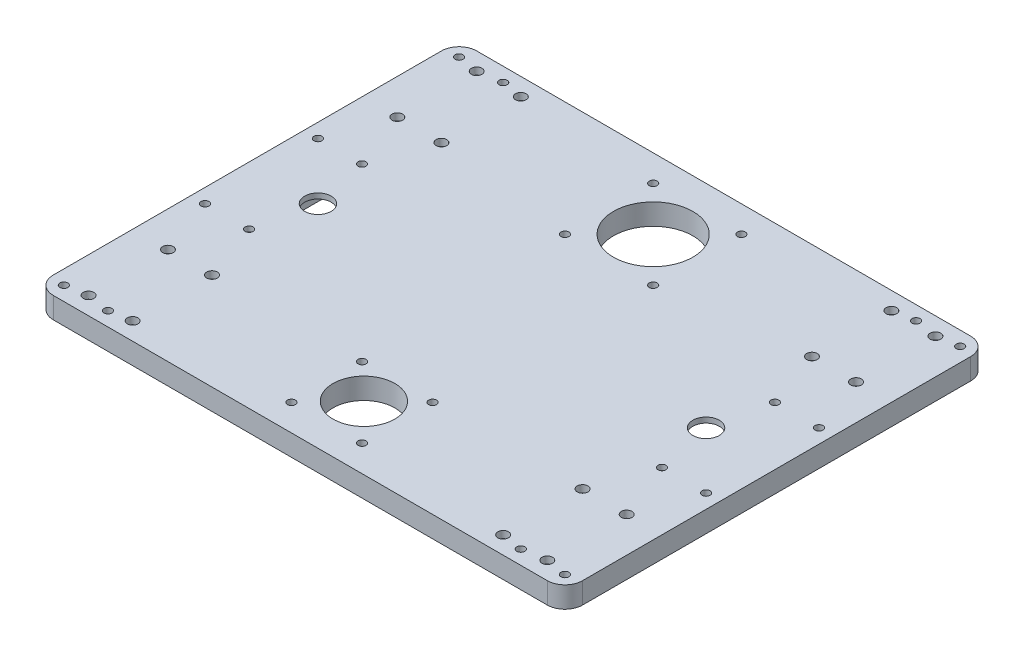
SolidWorks part; units mm, degrees
ref_plane "Front Plane" through (0, 0, 0) normal (0, 0, 1) x (1, 0, 0)
ref_plane "Top Plane" through (0, 0, 0) normal (0, 1, 0) x (1, 0, 0)
ref_plane "Right Plane" through (0, 0, 0) normal (1, 0, 0) x (0, 0, -1)
sketch "Sketch1" plane through (0, 0, 0) normal (0, 1, 0) x (1, 0, 0)
  line L1 (-150, 120) -> (150, 120)
  line L2 (-150, 120) -> (-150, -120)
  line L3 (-150, -120) -> (150, -120)
  line L4 (150, 120) -> (150, -120)
  dimension "D1" = 300
  dimension "D2" = 240
  dimension "D3" = 120
  dimension "D4" = 150
extrude "Boss-Extrude1" add sketch "Sketch1" along normal blind 12
sketch "Sketch2" plane through (0, 12, 0) normal (0, 1, 0) x (1, 0, 0)
  circle A0 centre (0, 80) radius 10
  dimension "D1" = 20
  dimension "D2" = 80
  dimension "D3" = 0
extrude "Cut-Extrude1" cut sketch "Sketch2" against normal blind 15
sketch "Sketch3" plane through (0, 12, 0) normal (0, 1, 0) x (1, 0, 0)
  circle A0 centre (25, 105) radius 2.25
  circle A1 centre (25, 55) radius 2.25
  circle A2 centre (-25, 105) radius 2.25
  circle A3 centre (-25, 55) radius 2.25
  circle A4 centre (0, 80) radius 10 construction
  dimension "D1" = 4.5
  dimension "D2" = 4.5
  dimension "D3" = 4.5
  dimension "D4" = 25
  dimension "D5" = 25
  dimension "D6" = 25
  dimension "D7" = 25
  dimension "D8" = 25
  dimension "D9" = 25
  dimension "D10" = 25
  dimension "D11" = 25
  dimension "D12" = 4.5
extrude "Cut-Extrude2" cut sketch "Sketch3" against normal blind 15
sketch "Sketch4" plane through (0, 12, 0) normal (0, 1, 0) x (1, 0, 0)
  line L0 (-150, 120) -> (-150, -120) construction
  line L1 (-150, -120) -> (150, -120) construction
  line L2 (150, 120) -> (-150, 120) construction
  line L3 (150, -120) -> (150, 120) construction
  circle A0 centre (-130, 110) radius 1.75
  circle A1 centre (-130, 65) radius 1.75
  circle A2 centre (-105, 110) radius 1.75
  circle A3 centre (-105, 65) radius 1.75
  circle A4 centre (-130, -65) radius 1.75
  circle A5 centre (-105, -65) radius 1.75
  circle A6 centre (-130, -110) radius 1.75
  circle A7 centre (-105, -110) radius 1.75
  circle A8 centre (105, -65) radius 1.75
  circle A9 centre (130, -65) radius 1.75
  circle A10 centre (105, -110) radius 1.75
  circle A11 centre (130, -110) radius 1.75
  circle A12 centre (105, 110) radius 1.75
  circle A13 centre (130, 110) radius 1.75
  circle A14 centre (105, 65) radius 1.75
  circle A15 centre (130, 65) radius 1.75
  dimension "D1" = 3.5
  dimension "D2" = 3.5
  dimension "D3" = 3.5
  dimension "D4" = 3.5
  dimension "D5" = 3.5
  dimension "D6" = 3.5
  dimension "D7" = 3.5
  dimension "D8" = 3.5
  dimension "D9" = 3.5
  dimension "D10" = 3.5
  dimension "D11" = 3.5
  dimension "D12" = 3.5
  dimension "D13" = 3.5
  dimension "D14" = 3.5
  dimension "D15" = 3.5
  dimension "D16" = 3.5
  dimension "D17" = 20
  dimension "D18" = 20
  dimension "D19" = 25
  dimension "D20" = 25
  dimension "D21" = 10
  dimension "D22" = 10
  dimension "D23" = 45
  dimension "D24" = 45
  dimension "D25" = 10
  dimension "D26" = 10
  dimension "D27" = 45
  dimension "D28" = 45
  dimension "D29" = 25
  dimension "D30" = 25
  dimension "D31" = 20
  dimension "D32" = 20
  dimension "D33" = 20
  dimension "D34" = 20
  dimension "D35" = 10
  dimension "D36" = 10
  dimension "D37" = 45
  dimension "D38" = 45
  dimension "D39" = 25
  dimension "D40" = 25
  dimension "D41" = 20
  dimension "D42" = 25
  dimension "D43" = 20
  dimension "D44" = 25
  dimension "D45" = 45
  dimension "D46" = 45
  dimension "D47" = 10
extrude "Cut-Extrude3" cut sketch "Sketch4" against normal blind 15
fillet "Fillet1" radius 10 1 edges at (150, 6, 120)
fillet "Fillet2" radius 10 1 edges at (-150, 6, 120)
fillet "Fillet3" radius 10 1 edges at (150, 6, -120)
fillet "Fillet4" radius 10 1 edges at (-150, 6, -120)
sketch "Sketch5" plane through (0, 12, 0) normal (0, 1, 0) x (1, 0, 0)
  line L0 (-140, -120) -> (140, -120) construction
  circle A0 centre (-20, -65) radius 2.25
  circle A1 centre (20, -65) radius 2.25
  circle A2 centre (-20, -105) radius 2.25
  circle A3 centre (20, -105) radius 2.25
  dimension "D1" = 4.5
  dimension "D2" = 4.5
  dimension "D3" = 4.5
  dimension "D4" = 4.5
  dimension "D5" = 15
  dimension "D7" = 20
  dimension "D8" = 20
  dimension "D10" = 20
  dimension "D11" = 40
  dimension "D12" = 40
  dimension "D6" = 15
  dimension "D9" = 20
extrude "Cut-Extrude4" cut sketch "Sketch5" against normal blind 15
sketch "Sketch6" plane through (0, 12, 0) normal (0, 1, 0) x (1, 0, 0)
  circle A0 centre (-130, 110) radius 3
  circle A1 centre (-105, 110) radius 3
  circle A2 centre (-105, 65) radius 3
  circle A3 centre (-130, 65) radius 3
  circle A4 centre (105, 110) radius 3
  circle A5 centre (130, 110) radius 3
  circle A6 centre (130, 65) radius 3
  circle A7 centre (105, 65) radius 3
  circle A8 centre (105, -65) radius 3
  circle A9 centre (130, -65) radius 3
  circle A10 centre (130, -110) radius 3
  circle A11 centre (105, -110) radius 3
  circle A12 centre (-130, -110) radius 3
  circle A13 centre (-105, -110) radius 3
  circle A14 centre (-105, -65) radius 3
  circle A15 centre (-130, -65) radius 3
  dimension "D1" = 6
  dimension "D2" = 6
  dimension "D3" = 6
  dimension "D4" = 6
  dimension "D5" = 6
  dimension "D6" = 6
  dimension "D7" = 6
  dimension "D8" = 6
  dimension "D9" = 6
  dimension "D10" = 6
  dimension "D11" = 6
  dimension "D12" = 6
  dimension "D13" = 6
  dimension "D14" = 6
  dimension "D15" = 6
  dimension "D16" = 6
extrude "Cut-Extrude5" cut sketch "Sketch6" against normal blind 4
sketch "Sketch8" plane through (0, 0, 0) normal (0, -1, 0) x (-1, 0, 0)
  line L1 (120, -50) -> (-120, -50)
  line L2 (120, -50) -> (120, 50)
  line L3 (120, 50) -> (-120, 50)
  line L4 (-120, -50) -> (-120, 50)
  dimension "D1" = 240
  dimension "D2" = 100
  dimension "D3" = 50
  dimension "D4" = 120
extrude "Cut-Extrude6" cut sketch "Sketch8" against normal blind 9
fillet "Fillet5" radius 10 1 edges at (-120, 4.5, 50)
fillet "Fillet6" radius 10 1 edges at (120, 4.5, 50)
fillet "Fillet7" radius 10 1 edges at (120, 4.5, -50)
fillet "Fillet8" radius 10 1 edges at (-120, 4.5, -50)
sketch "Sketch9" plane through (0, 12, 0) normal (0, 1, 0) x (1, 0, 0)
  line L0 (-150, 110) -> (-150, -110) construction
  line L1 (-140, -120) -> (140, -120) construction
  line L2 (150, -110) -> (150, 110) construction
  line L3 (140, 120) -> (-140, 120) construction
  circle A0 centre (-142, 112) radius 2.25
  circle A1 centre (-142, -112) radius 2.25
  circle A2 centre (142, -112) radius 2.25
  circle A3 centre (142, 112) radius 2.25
  dimension "D1" = 4.5
  dimension "D2" = 4.5
  dimension "D3" = 4.5
  dimension "D4" = 4.5
  dimension "D5" = 8
  dimension "D6" = 8
  dimension "D7" = 8
  dimension "D8" = 8
  dimension "D9" = 8
  dimension "D10" = 8
  dimension "D11" = 8
  dimension "D12" = 8
extrude "Cut-Extrude7" cut sketch "Sketch9" against normal blind 15
sketch "Sketch10" plane through (0, 12, 0) normal (0, 1, 0) x (1, 0, 0)
  line L1 (-140, -120) -> (140, -120) construction
  line L2 (140, 120) -> (-140, 120) construction
  circle A1 centre (-117, -112) radius 2.25
  circle A2 centre (-117, 112) radius 2.25
  circle A3 centre (117, 112) radius 2.25
  circle A4 centre (117, -112) radius 2.25
  circle A5 centre (-142, 112) radius 2.25 construction
  circle A6 centre (-142, -112) radius 2.25 construction
  circle A7 centre (142, -112) radius 2.25 construction
  circle A8 centre (142, 112) radius 2.25 construction
  dimension "D1" = 4.5
  dimension "D2" = 4.5
  dimension "D3" = 4.5
  dimension "D4" = 4.5
  dimension "D5" = 8
  dimension "D6" = 8
  dimension "D7" = 8
  dimension "D8" = 8
  dimension "D9" = 25
  dimension "D10" = 25
  dimension "D11" = 25
  dimension "D12" = 25
extrude "Cut-Extrude8" cut sketch "Sketch10" against normal blind 15
sketch "Sketch12" plane through (0, 12, 0) normal (0, 1, 0) x (1, 0, 0)
  circle A0 centre (110, 0) radius 7.5
  circle A1 centre (-110, 0) radius 7.5
  dimension "D1" = 15
  dimension "D2" = 15
  dimension "D3" = 110
  dimension "D4" = 110
extrude "Cut-Extrude9" cut sketch "Sketch12" against normal blind 15
sketch "Sketch13" plane through (0, 0, 0) normal (0, -1, 0) x (-1, 0, 0)
  line L0 (-110, -50) -> (110, -50) construction
  line L1 (35, -50) -> (85, -50)
  line L2 (35, -50) -> (35, -110)
  line L3 (35, -110) -> (85, -110)
  line L4 (85, -50) -> (85, -110)
  line L5 (-110, -50) -> (110, -50) construction
  line L6 (-85, -50) -> (-35, -50)
  line L7 (-85, -50) -> (-85, -110)
  line L8 (-85, -110) -> (-35, -110)
  line L9 (-35, -50) -> (-35, -110)
  line L10 (110, 50) -> (-110, 50) construction
  line L11 (-35, 50) -> (-85, 50)
  line L12 (-35, 50) -> (-35, 110)
  line L13 (-35, 110) -> (-85, 110)
  line L14 (-85, 50) -> (-85, 110)
  line L15 (-140, 120) -> (140, 120) construction
  line L16 (85, 50) -> (35, 50)
  line L17 (85, 50) -> (85, 110)
  line L18 (85, 110) -> (35, 110)
  line L19 (35, 50) -> (35, 110)
  line L20 (140, -120) -> (-140, -120) construction
  dimension "D1" = 10
  dimension "D2" = 10
  dimension "D3" = 10
  dimension "D4" = 10
  dimension "D5" = 35
  dimension "D6" = 35
  dimension "D7" = 50
  dimension "D8" = 50
  dimension "D9" = 50
  dimension "D10" = 50
  dimension "D11" = 35
  dimension "D12" = 35
extrude "Cut-Extrude10" cut sketch "Sketch13" against normal blind 9
fillet "Fillet9" radius 10 1 edges at (-85, 4.5, 110)
fillet "Fillet10" radius 10 1 edges at (-35, 4.5, 110)
fillet "Fillet11" radius 10 1 edges at (85, 4.5, 110)
fillet "Fillet12" radius 10 1 edges at (35, 4.5, 110)
fillet "Fillet13" radius 10 1 edges at (85, 4.5, -110)
fillet "Fillet14" radius 10 1 edges at (35, 4.5, -110)
fillet "Fillet15" radius 10 1 edges at (-35, 4.5, -110)
fillet "Fillet16" radius 10 1 edges at (-85, 4.5, -110)
fillet "Fillet17" radius 10 1 edges at (35, 4.5, -50)
fillet "Fillet18" radius 10 1 edges at (-35, 4.5, -50)
fillet "Fillet19" radius 10 1 edges at (35, 4.5, 50)
fillet "Fillet20" radius 10 1 edges at (-35, 4.5, 50)
fillet "Fillet21" radius 10 1 edges at (85, 4.5, 50)
fillet "Fillet22" radius 10 1 edges at (85, 4.5, -50)
fillet "Fillet23" radius 10 1 edges at (-85, 4.5, 50)
fillet "Fillet24" radius 10 1 edges at (-85, 4.5, -50)
sketch "Sketch14" plane through (0, 12, 0) normal (0, 1, 0) x (1, 0, 0)
  circle A0 centre (-142, 32) radius 2.25
  circle A1 centre (-117, 32) radius 2.25
  circle A2 centre (-142, -32) radius 2.25
  circle A3 centre (-117, -32) radius 2.25
  circle A4 centre (117, -32) radius 2.25
  circle A5 centre (142, -32) radius 2.25
  circle A6 centre (117, 32) radius 2.25
  circle A7 centre (142, 32) radius 2.25
  circle A8 centre (117, 112) radius 2.25 construction
  circle A9 centre (142, 112) radius 2.25 construction
  circle A10 centre (117, -112) radius 2.25 construction
  circle A11 centre (142, -112) radius 2.25 construction
  circle A12 centre (-142, 112) radius 2.25 construction
  circle A13 centre (-142, -112) radius 2.25 construction
  circle A14 centre (-117, 112) radius 2.25 construction
  circle A15 centre (-117, -112) radius 2.25 construction
  dimension "D1" = 4.5
  dimension "D2" = 4.5
  dimension "D3" = 4.5
  dimension "D4" = 4.5
  dimension "D5" = 4.5
  dimension "D6" = 4.5
  dimension "D7" = 4.5
  dimension "D8" = 4.5
  dimension "D9" = 0
  dimension "D10" = 0
  dimension "D11" = 25
  dimension "D12" = 25
  dimension "D13" = 80
  dimension "D14" = 80
  dimension "D15" = 80
  dimension "D16" = 80
  dimension "D17" = 80
  dimension "D18" = 80
  dimension "D19" = 0
  dimension "D20" = 0
  dimension "D21" = 80
  dimension "D23" = 0
  dimension "D24" = 0
  dimension "D22" = 80
extrude "Cut-Extrude11" cut sketch "Sketch14" against normal blind 13
sketch "Sketch15" plane through (0, 0, 0) normal (0, -1, 0) x (-1, 0, 0)
  line L1 (145, 71) -> (90, 71)
  line L2 (145, 71) -> (145, 106)
  line L3 (145, 106) -> (90, 106)
  line L4 (90, 71) -> (90, 106)
  line L6 (-140, 120) -> (140, 120) construction
  line L7 (150, 110) -> (150, -110) construction
  dimension "D1" = 55
  dimension "D2" = 35
  dimension "D3" = 14
  dimension "D4" = 5
extrude "Cut-Extrude12" cut sketch "Sketch15" against normal blind 8
sketch "Sketch16" plane through (0, 0, 0) normal (0, -1, 0) x (-1, 0, 0)
  line L1 (145, -105) -> (90, -105)
  line L2 (145, -105) -> (145, -70)
  line L3 (145, -70) -> (90, -70)
  line L4 (90, -105) -> (90, -70)
  line L6 (140, -120) -> (-140, -120) construction
  line L7 (150, 110) -> (150, -110) construction
  dimension "D1" = 55
  dimension "D2" = 35
  dimension "D3" = 15
  dimension "D4" = 5
extrude "Cut-Extrude13" cut sketch "Sketch16" against normal blind 8
sketch "Sketch17" plane through (0, 0, 0) normal (0, -1, 0) x (-1, 0, 0)
  line L0 (-150, -110) -> (-150, 110) construction
  line L1 (-145, -106) -> (-90, -106)
  line L2 (-145, -106) -> (-145, -73.6882)
  line L3 (-145, -73.6882) -> (-90, -73.6882)
  line L4 (-90, -106) -> (-90, -73.6882)
  line L5 (140, -120) -> (-140, -120) construction
  dimension "D1" = 55
  dimension "D2" = 5
  dimension "D3" = 14
extrude "Cut-Extrude14" cut sketch "Sketch17" against normal blind 8
sketch "Sketch18" plane through (0, 0, 0) normal (0, -1, 0) x (-1, 0, 0)
  line L0 (-150, -110) -> (-150, 110) construction
  line L1 (-145, 71) -> (-90, 71)
  line L2 (-145, 71) -> (-145, 106)
  line L3 (-145, 106) -> (-90, 106)
  line L4 (-90, 71) -> (-90, 106)
  line L5 (-140, 120) -> (140, 120) construction
  dimension "D1" = 55
  dimension "D2" = 5
  dimension "D3" = 35
  dimension "D4" = 14
extrude "Cut-Extrude15" cut sketch "Sketch18" against normal blind 8
sketch "Sketch22" plane through (0, 0, 0) normal (0, -1, 0) x (-1, 0, 0)
  circle A0 centre (0, -83.9273) radius 17.5
  dimension "D1" = 35
extrude "Cut-Extrude17" cut sketch "Sketch22" against normal blind 12
sketch "Sketch23" plane through (0, 0, 0) normal (0, -1, 0) x (-1, 0, 0)
  line L0 (120, -40) -> (120, 40) construction
  line L1 (143, -25) -> (120, -25)
  line L2 (143, -25) -> (143, 20)
  line L3 (143, 20) -> (120, 20)
  line L4 (120, -25) -> (120, 20)
  line L5 (-120, 40) -> (-120, -40) construction
  line L6 (-143, -25) -> (-120, -25)
  line L7 (-143, -25) -> (-143, 20)
  line L8 (-143, 20) -> (-120, 20)
  line L9 (-120, -25) -> (-120, 20)
  line L10 (150, 110) -> (150, -110) construction
  line L11 (-150, -110) -> (-150, 110) construction
  circle A0 centre (142, -32) radius 2.25 construction
  circle A2 centre (-142, -32) radius 2.25 construction
  dimension "D6" = 7
  dimension "D1" = 7
  dimension "D2" = 7
  dimension "D3" = 45
  dimension "D4" = 45
  dimension "D5" = 7
extrude "Cut-Extrude18" cut sketch "Sketch23" against normal blind 3
sketch "Sketch24" plane through (0, 0, 0) normal (0, -1, 0) x (-1, 0, 0)
  circle A0 centre (0, 80) radius 22.5
  dimension "D1" = 45
extrude "Cut-Extrude19" cut sketch "Sketch24" against normal blind 12
fillet "Fillet25" radius 10 1 edges at (-145, 4, -71)
fillet "Fillet26" radius 10 1 edges at (-145, 4, -106)
fillet "Fillet27" radius 10 1 edges at (-145, 4, 105)
fillet "Fillet28" radius 10 1 edges at (145, 4, 106)
fillet "Fillet29" radius 10 1 edges at (145, 4, 73.6882)
fillet "Fillet30" radius 10 1 edges at (-145, 4, 70)
fillet "Fillet31" radius 10 1 edges at (145, 4, -71)
fillet "Fillet32" radius 10 1 edges at (145, 4, -106)
